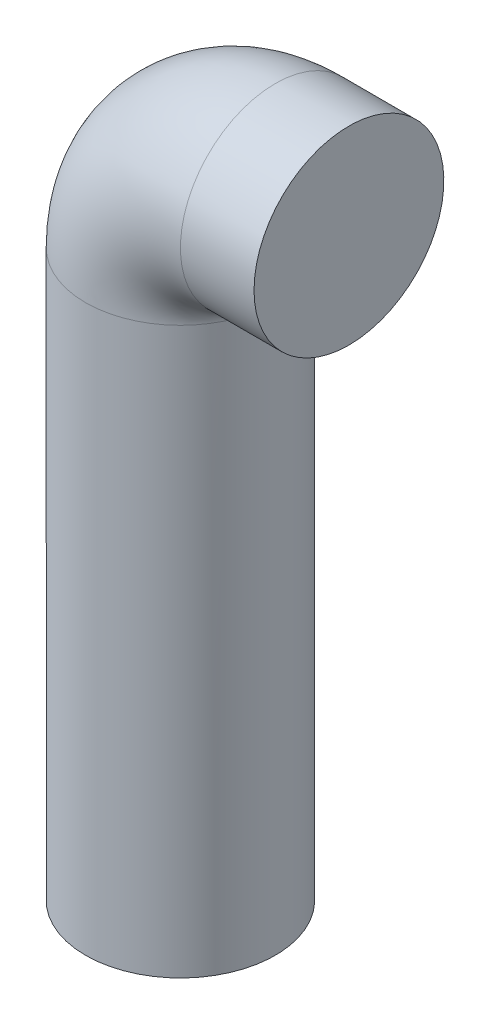
SolidWorks part; units mm, degrees
ref_plane "Front Plane" through (0, 0, 0) normal (0, 0, 1) x (1, 0, 0)
ref_plane "Top Plane" through (0, 0, 0) normal (0, 1, 0) x (1, 0, 0)
ref_plane "Right Plane" through (0, 0, 0) normal (1, 0, 0) x (0, 0, -1)
sketch "Sketch4" plane through (0, 0, 0) normal (0, 0, 1) x (1, 0, 0)
  line L0 (0, 0) -> (0, 148.9)
  line L1 (25, 173.9) -> (44.39, 173.9)
  arc A0 (0, 148.9) -> (25, 173.9) centre (25, 148.9) cw
  point P7 (0, 173.9)
  dimension "D3" = 25
  dimension "D1" = 173.9
  dimension "D2" = 44.39
sketch "Sketch5" plane through (0, 0, 0) normal (0, 1, 0) x (1, 0, 0)
  circle A0 centre (0, 0) radius 25
  dimension "D1" = 50
sweep "Sweep2" add profiles "Sketch5" path "Sketch4"
